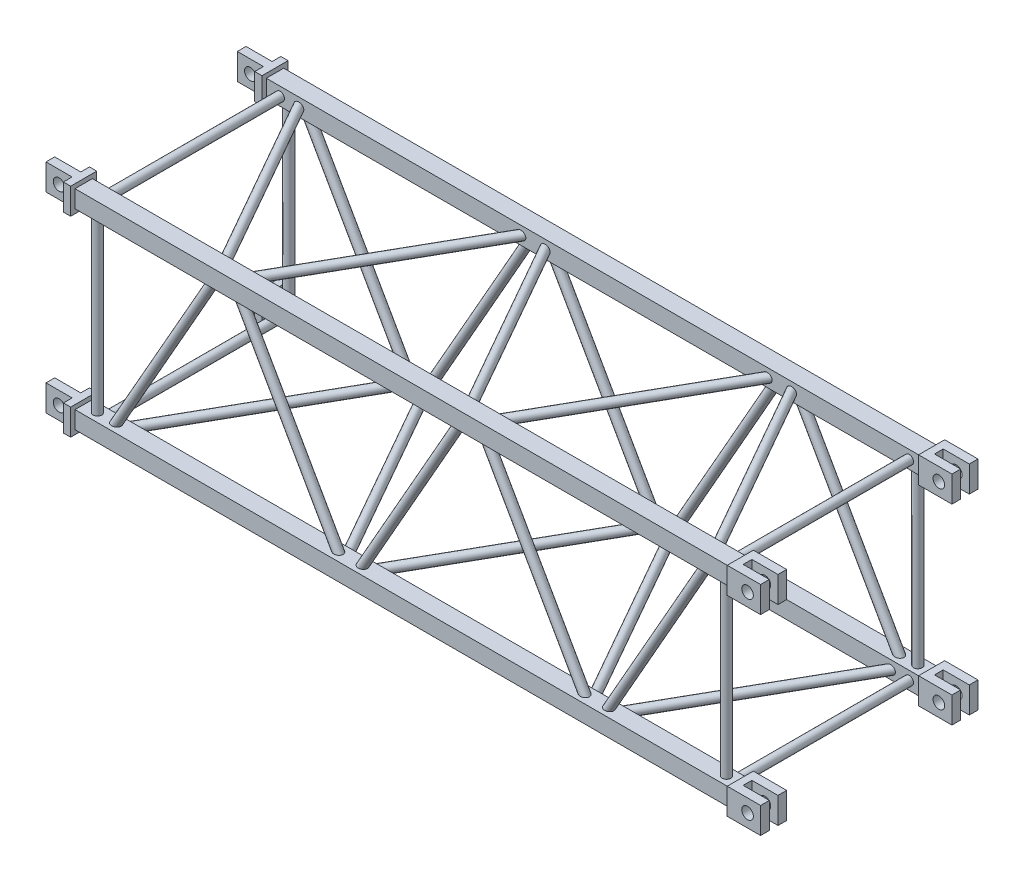
SolidWorks part; units mm, degrees
ref_plane "Front Plane" through (0, 0, 0) normal (0, 0, 1) x (1, 0, 0)
ref_plane "Top Plane" through (0, 0, 0) normal (0, 1, 0) x (1, 0, 0)
ref_plane "Right Plane" through (0, 0, 0) normal (1, 0, 0) x (0, 0, -1)
sketch "Sketch1" plane through (0, 0, 0) normal (0, 0, 1) x (1, 0, 0)
  line L0 (-226.5, 66) -> (226.5, 66)
  line L1 (0, 0) -> (-97.0714, 0) construction
  line L2 (-226.5, -66) -> (226.5, -66)
  line L3 (-217, 66) -> (-217, -66)
  line L4 (217, 66) -> (217, -66)
  line L5 (-207.5, -66) -> (-132.5, 66)
  line L6 (-122.5, 66) -> (-47.5, -66)
  line L7 (-37.5, -66) -> (37.5, 66)
  line L8 (47.5, 66) -> (122.5, -66)
  line L9 (132.5, -66) -> (207.5, 66)
  point P2 (0, 66)
  dimension "D1" = 453
  dimension "D2" = 66
  dimension "D3" = 9.5
  dimension "D4" = 9.5
  dimension "D5" = 9.5
  dimension "D6" = 75
  dimension "D7" = 10
  dimension "D8" = 10
  dimension "D9" = 75
  dimension "D10" = 10
  dimension "D11" = 75
  dimension "D12" = 75
  dimension "D13" = 10
  dimension "D14" = 75
ref_plane "Plane1" through (0, 0, -132) normal (0, 0, 1) x (1, 0, 0)
sketch "Sketch2" plane through (0, 0, -132) normal (0, 0, 1) x (1, 0, 0)
  line L0 (217, 66) -> (217, -66) construction
  line L1 (-226.5, -66) -> (226.5, -66) construction
  line L2 (-217, 66) -> (-217, -66) construction
  line L3 (-226.5, 66) -> (226.5, 66) construction
  line L4 (217, 66) -> (217, -66)
  line L5 (-226.5, -66) -> (226.5, -66)
  line L6 (-217, 66) -> (-217, -66)
  line L7 (-226.5, 66) -> (226.5, 66)
  line L8 (-207.5, 66) -> (-132.5, -66)
  line L9 (-122.5, -66) -> (-47.5, 66)
  line L10 (-37.5, 66) -> (37.5, -66)
  line L11 (47.5, -66) -> (122.5, 66)
  line L12 (132.5, 66) -> (207.5, -66)
  dimension "D1" = 9.5
  dimension "D2" = 75
  dimension "D3" = 10
  dimension "D4" = 75
  dimension "D5" = 10
  dimension "D6" = 75
  dimension "D7" = 75
  dimension "D8" = 75
  dimension "D9" = 10
  dimension "D10" = 10
ref_plane "Plane4" through (0, 66, 0) normal (0, -1, 0) x (-1, 0, 0)
sketch "Sketch5" plane through (0, 66, 0) normal (0, -1, 0) x (-1, 0, 0)
  line L0 (217, 0) -> (217, 132)
  line L1 (-217, 0) -> (-217, 132)
  line L2 (207.5, 132) -> (132.5, 0)
  line L3 (122.5, 0) -> (47.5, 132)
  line L4 (37.5, 132) -> (-37.5, 0)
  line L5 (-47.5, 0) -> (-122.5, 132)
  line L6 (-132.5, 132) -> (-207.5, 0)
  point P0 (217, 0)
  point P2 (217, 132)
  point P4 (-217, 132)
  point P6 (-217, 0)
  point P12 (207.5, 132)
  point P13 (-37.5, 0)
  point P16 (-47.5, 0)
  point P18 (-207.5, 0)
  point P20 (-132.5, 132)
  point P22 (-122.5, 132)
  point P24 (37.5, 132)
  point P26 (47.5, 132)
  point P28 (122.5, 0)
  point P30 (132.5, 0)
ref_plane "Plane5" through (0, 0, -132) normal (0, 0, 1) x (1, 0, 0)
ref_plane "Plane6" through (0, -66, 0) normal (0, -1, 0) x (-1, 0, 0)
sketch "Sketch7" plane through (0, -66, 0) normal (0, -1, 0) x (-1, 0, 0)
  line L0 (217, 0) -> (217, 132) construction
  line L1 (-217, 0) -> (-217, 132) construction
  line L2 (217, 0) -> (217, 132)
  line L3 (-217, 0) -> (-217, 132)
  line L4 (132.5, 132) -> (207.5, 0)
  line L5 (122.5, 132) -> (47.5, 0)
  line L6 (37.5, 0) -> (-37.5, 132)
  line L7 (-47.5, 132) -> (-122.5, 0)
  line L8 (-132.5, 0) -> (-207.5, 132)
  point P4 (-207.5, 132)
  point P6 (-132.5, 0)
  point P8 (-122.5, 0)
  point P10 (-47.5, 132)
  point P12 (-37.5, 132)
  point P14 (37.5, 0)
  point P16 (47.5, 0)
  point P18 (207.5, 0)
  point P20 (122.5, 132)
  point P22 (132.5, 132)
other "Sq section 12X12X1.1(1)"
ref_plane "Plane7" through (-226.5, 66, -132) normal (1, 0, 0) x (0, 1, 0)
sketch "Sketch11" plane through (-226.5, 66, -132) normal (1, 0, 0) x (0, 1, 0)
  line L0 (4.9, 4.9) -> (-4.9, 4.9)
  line L1 (6, -6) -> (-6, -6)
  line L2 (6, -6) -> (6, 6)
  line L3 (6, 6) -> (-6, 6)
  line L4 (-6, -6) -> (-6, 6)
  line L5 (6, -6) -> (-6, 6) construction
  line L6 (6, 6) -> (-6, -6) construction
  line L7 (-4.9, -4.9) -> (-4.9, 4.9)
  line L8 (4.9, -4.9) -> (-4.9, -4.9)
  line L9 (4.9, -4.9) -> (4.9, 4.9)
  point P0 (0, 0)
  point P10 (0, 0)
  dimension "D1" = 12
  dimension "D2" = 12
  dimension "D3" = 1.1
other "Round section 6X1.1 CR(1)"
ref_plane "Plane8" through (-217, 66, 0) normal (0, 0, -1) x (1, 0, 0)
sketch "Sketch12" plane through (-217, 66, 0) normal (0, 0, -1) x (1, 0, 0)
  circle A0 centre (0, 0) radius 3
  circle A1 centre (0, 0) radius 1.9
  point P5 (0, 0)
  dimension "D1" = 6
  dimension "D2" = 1.1
other "Round section 6X1.1 CR(2)"
ref_plane "Plane9" through (217, 66, -132) normal (0, -1, 0) x (1, 0, 0)
sketch "Sketch13" plane through (217, 66, -132) normal (0, -1, 0) x (1, 0, 0)
  circle A0 centre (0, 0) radius 3
  circle A1 centre (0, 0) radius 1.9
  point P5 (0, 0)
  dimension "D1" = 6
  dimension "D2" = 1.1
other "Trim/Extend1"
other "Trim/Extend2"
other "Trim/Extend3"
other "Round section 6X1.1 CR(3)"
ref_plane "Plane10" through (-207.5, -66, 0) normal (0.494, 0.8695, 0) x (-0.8695, 0.494, 0)
sketch "Sketch14" plane through (-207.5, -66, 0) normal (0.494, 0.8695, 0) x (-0.8695, 0.494, 0)
  circle A0 centre (0, 0) radius 3
  circle A1 centre (0, 0) radius 1.9
  point P5 (0, 0)
  dimension "D1" = 6
  dimension "D2" = 1.1
other "Round section 6X1.1 CR(4)"
ref_plane "Plane11" through (-122.5, 66, 0) normal (0.494, -0.8695, 0) x (0.8695, 0.494, 0)
sketch "Sketch15" plane through (-122.5, 66, 0) normal (0.494, -0.8695, 0) x (0.8695, 0.494, 0)
  circle A0 centre (0, 0) radius 3
  circle A1 centre (0, 0) radius 1.9
  point P5 (0, 0)
  dimension "D1" = 6
  dimension "D2" = 1.1
other "Trim/Extend4"
other "Round section 6X1.1 CR(5)"
ref_plane "Plane12" through (-132.5, -66, -132) normal (-0.494, 0, 0.8695) x (-0.8695, 0, -0.494)
sketch "Sketch16" plane through (-132.5, -66, -132) normal (-0.494, 0, 0.8695) x (-0.8695, 0, -0.494)
  circle A0 centre (0, 0) radius 3
  circle A1 centre (0, 0) radius 1.9
  point P5 (0, 0)
  dimension "D1" = 6
  dimension "D2" = 1.1
other "Round section 6X1.1 CR(6)"
ref_plane "Plane13" through (-122.5, -66, -132) normal (0.494, 0, 0.8695) x (-0.8695, 0, 0.494)
sketch "Sketch17" plane through (-122.5, -66, -132) normal (0.494, 0, 0.8695) x (-0.8695, 0, 0.494)
  circle A0 centre (0, 0) radius 3
  circle A1 centre (0, 0) radius 1.9
  point P5 (0, 0)
  dimension "D1" = 6
  dimension "D2" = 1.1
other "Trim/Extend5"
other "Round section 6X1.1 CR(7)"
ref_plane "Plane14" through (-207.5, 66, -132) normal (0.494, -0.8695, 0) x (0.8695, 0.494, 0)
sketch "Sketch19" plane through (-207.5, 66, -132) normal (0.494, -0.8695, 0) x (0.8695, 0.494, 0)
  circle A0 centre (0, 0) radius 3
  circle A1 centre (0, 0) radius 1.9
  point P5 (0, 0)
  dimension "D1" = 6
  dimension "D2" = 1.1
other "Round section 6X1.1 CR(8)"
ref_plane "Plane15" through (-122.5, -66, -132) normal (0.494, 0.8695, 0) x (-0.8695, 0.494, 0)
sketch "Sketch110" plane through (-122.5, -66, -132) normal (0.494, 0.8695, 0) x (-0.8695, 0.494, 0)
  circle A0 centre (0, 0) radius 3
  circle A1 centre (0, 0) radius 1.9
  point P5 (0, 0)
  dimension "D1" = 6
  dimension "D2" = 1.1
other "Trim/Extend8"
other "Round section 6X1.1 CR(9)"
ref_plane "Plane16" through (132.5, 66, -132) normal (0.494, 0, 0.8695) x (-0.8695, 0, 0.494)
sketch "Sketch111" plane through (132.5, 66, -132) normal (0.494, 0, 0.8695) x (-0.8695, 0, 0.494)
  circle A0 centre (0, 0) radius 3
  circle A1 centre (0, 0) radius 1.9
  point P5 (0, 0)
  dimension "D1" = 6
  dimension "D2" = 1.1
other "Round section 6X1.1 CR(10)"
ref_plane "Plane17" through (47.5, 66, 0) normal (0.494, 0, -0.8695) x (0.8695, 0, 0.494)
sketch "Sketch112" plane through (47.5, 66, 0) normal (0.494, 0, -0.8695) x (0.8695, 0, 0.494)
  circle A0 centre (0, 0) radius 3
  circle A1 centre (0, 0) radius 1.9
  point P5 (0, 0)
  dimension "D1" = 6
  dimension "D2" = 1.1
other "Trim/Extend9"
sketch "Sketch114" plane through (226.5, 0, 0) normal (1, 0, 0) x (0, 0, -1)
  line L20 (0, 0) -> (40.2543, 0) construction
  line L21 (123, 75) -> (141, 75)
  line L22 (123, 75) -> (123, 57)
  line L23 (123, 57) -> (141, 57)
  line L24 (141, 75) -> (141, 57)
  line L25 (123, 75) -> (141, 57) construction
  line L26 (123, 57) -> (141, 75) construction
  line L27 (141, -75) -> (141, -57)
  line L28 (123, -57) -> (141, -57)
  line L29 (123, -75) -> (123, -57)
  line L30 (123, -75) -> (141, -75)
  line L31 (66, 69) -> (66, 81.2876) construction
  line L32 (126, 69) -> (6, 69) construction
  line L33 (9, -75) -> (9, -57)
  line L34 (9, -75) -> (-9, -75)
  line L35 (-9, -75) -> (-9, -57)
  line L36 (9, -57) -> (-9, -57)
  line L37 (9, 57) -> (-9, 57)
  line L38 (9, 75) -> (9, 57)
  line L39 (9, 75) -> (-9, 75)
  line L40 (-9, 75) -> (-9, 57)
  point P0 (-21.5566, -54.522)
  point P1 (-21.5566, -54.522)
  point P2 (132, 66)
  dimension "D1" = 18
  dimension "D2" = 18
extrude "Boss-Extrude1" add sketch "Sketch114" along normal blind 23 separate body
sketch "Sketch115" plane through (0, 0, -141) normal (0, 0, -1) x (-1, 0, 0)
  line L0 (-249.5, 57) -> (-249.5, 75) construction
  line L1 (-249.5, 75) -> (-226.5, 75) construction
  line L2 (-249.5, -75) -> (-249.5, -57) construction
  line L3 (-249.5, -57) -> (-226.5, -57) construction
  circle A0 centre (-240.5, 66) radius 4
  circle A1 centre (-240.5, -66) radius 4
  dimension "D3" = 8
  dimension "D4" = 8
  dimension "D1" = 9
  dimension "D2" = 9
  dimension "D5" = 9
  dimension "D6" = 9
extrude "Cut-Extrude1" cut sketch "Sketch115" against normal through all
sketch "Sketch116" plane through (0, 75, 0) normal (0, 1, 0) x (1, 0, 0)
  line L0 (249.5, -9) -> (226.5, -9) construction
  line L1 (258.0613, 3) -> (231.5, 3)
  line L2 (258.0613, 3) -> (258.0613, -3)
  line L3 (258.0613, -3) -> (231.5, -3)
  line L4 (231.5, 3) -> (231.5, -3)
  line L5 (249.5, 9) -> (226.5, 9) construction
  line L6 (249.5, 9) -> (249.5, -9) construction
  line L7 (220, 66) -> (258.0613, 66) construction
  line L8 (220, 6) -> (220, 126) construction
  line L9 (231.5, 129) -> (231.5, 135)
  line L10 (258.0613, 135) -> (231.5, 135)
  line L11 (258.0613, 129) -> (231.5, 129)
  line L12 (258.0613, 129) -> (258.0613, 135)
  dimension "D1" = 6
  dimension "D2" = 6
  dimension "D3" = 18
extrude "Cut-Extrude2" cut sketch "Sketch116" against normal through all
sketch "Sketch117" plane through (-226.5, 0, 0) normal (-1, 0, 0) x (0, 0, 1)
  line L0 (0, 0) -> (-57.6207, 0) construction
  line L1 (-141, 57) -> (-123, 57)
  line L2 (-141, 57) -> (-141, 75)
  line L3 (-141, 75) -> (-123, 75)
  line L4 (-123, 57) -> (-123, 75)
  line L5 (-141, 57) -> (-123, 75) construction
  line L6 (-141, 75) -> (-123, 57) construction
  line L7 (-123, -57) -> (-123, -75)
  line L8 (-141, -57) -> (-123, -57)
  line L9 (-141, -57) -> (-141, -75)
  line L10 (-141, -75) -> (-123, -75)
  line L11 (-66, 69) -> (-66, 100.7205) construction
  line L12 (-6, 69) -> (-126, 69) construction
  line L13 (-9, 57) -> (-9, 75)
  line L14 (9, 57) -> (-9, 57)
  line L15 (9, 57) -> (9, 75)
  line L16 (9, 75) -> (-9, 75)
  line L17 (9, -57) -> (-9, -57)
  line L18 (9, -57) -> (9, -75)
  line L19 (-9, -57) -> (-9, -75)
  line L20 (9, -75) -> (-9, -75)
  point P0 (-132, 66)
  dimension "D1" = 18
  dimension "D2" = 18
extrude "Boss-Extrude2" add sketch "Sketch117" along normal blind 23 separate body
sketch "Sketch118" plane through (0, 75, 0) normal (0, 1, 0) x (1, 0, 0)
  line L0 (-249.5, 141) -> (-226.5, 141) construction
  line L9 (-258.2738, 141) -> (-231.5, 141)
  line L10 (-258.2738, 141) -> (-258.2738, 135)
  line L11 (-258.2738, 135) -> (-231.5, 135)
  line L12 (-231.5, 141) -> (-231.5, 135)
  line L13 (-231.5, 129) -> (-258.2738, 129)
  line L14 (-231.5, 129) -> (-231.5, 123)
  line L15 (-231.5, 123) -> (-258.2738, 123)
  line L16 (-258.2738, 129) -> (-258.2738, 123)
  line L25 (-249.5, 123) -> (-226.5, 123) construction
  line L26 (-226.5, 123) -> (-226.5, 141) construction
  line L27 (-220, 66) -> (-285.5331, 66) construction
  line L28 (-220, 126) -> (-220, 6) construction
  line L29 (-258.2738, 3) -> (-258.2738, 9)
  line L30 (-231.5, 9) -> (-258.2738, 9)
  line L31 (-231.5, 3) -> (-258.2738, 3)
  line L32 (-231.5, 3) -> (-231.5, 9)
  line L33 (-231.5, -9) -> (-231.5, -3)
  line L34 (-258.2738, -9) -> (-258.2738, -3)
  line L35 (-258.2738, -3) -> (-231.5, -3)
  line L36 (-258.2738, -9) -> (-231.5, -9)
  dimension "D1" = 6
  dimension "D2" = 5
  dimension "D3" = 6
extrude "Cut-Extrude3" cut sketch "Sketch118" against normal through all
sketch "Sketch119" plane through (0, 0, 3) normal (0, 0, 1) x (1, 0, 0)
  line L0 (-249.5, 57) -> (-249.5, 75) construction
  line L1 (-231.5, 57) -> (-249.5, 57) construction
  line L2 (-220, 0) -> (-287.5111, 0) construction
  line L3 (-220, 60) -> (-220, -60) construction
  circle A0 centre (-240.5, 66) radius 4
  circle A1 centre (-240.5, -66) radius 4
  dimension "D1" = 8
  dimension "D2" = 9
  dimension "D3" = 9
extrude "Cut-Extrude4" cut sketch "Sketch119" against normal through all
